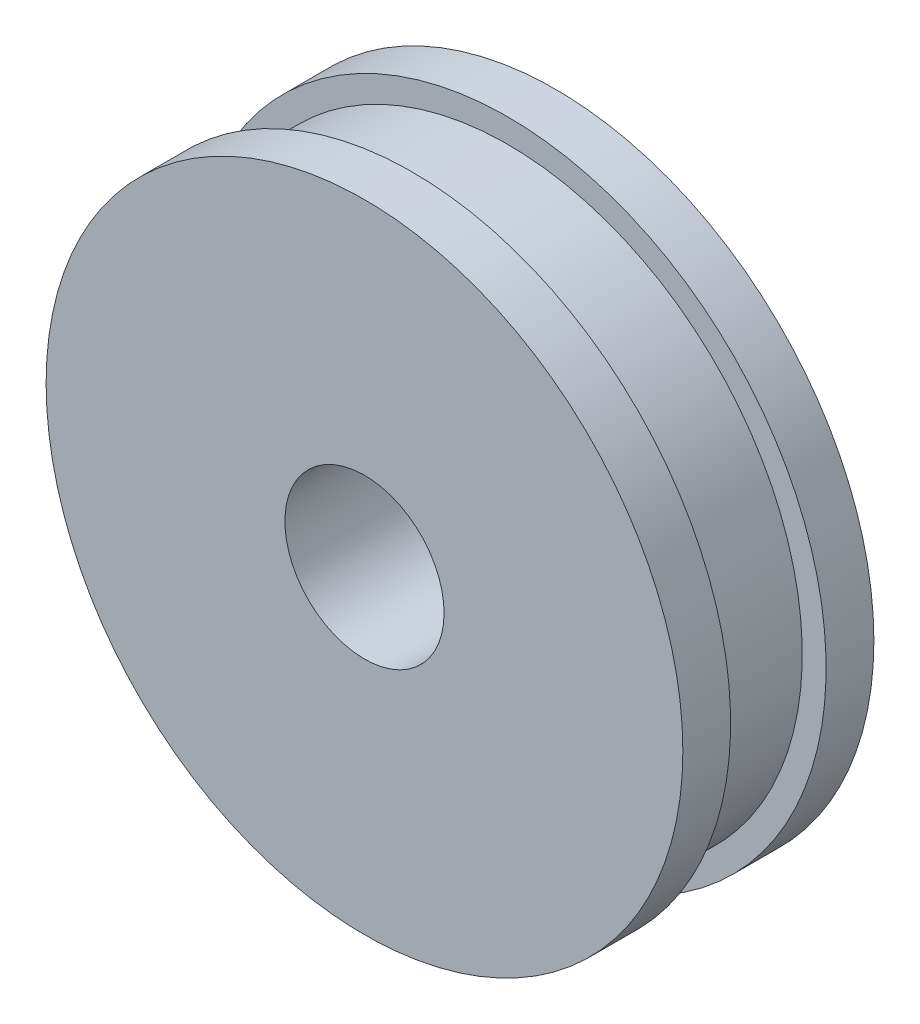
SolidWorks part; units mm, degrees
material "Alumina"
ref_plane "Front Plane" through (0, 0, 0) normal (0, 0, 1) x (1, 0, 0)
ref_plane "Top Plane" through (0, 0, 0) normal (0, 1, 0) x (1, 0, 0)
ref_plane "Right Plane" through (0, 0, 0) normal (1, 0, 0) x (0, 0, -1)
sketch "Sketch1" plane through (0, 0, 0) normal (0, 0, 1) x (1, 0, 0)
  circle A0 centre (0, 0) radius 5
  circle A1 centre (0, 0) radius 20
  dimension "D1" = 10
  dimension "D2" = 40
extrude "Boss-Extrude1" add sketch "Sketch1" along normal blind 12
sketch "Sketch2" plane through (0, 0, 0) normal (0, 1, 0) x (1, 0, 0)
  line L0 (0, 8.6021) -> (0, -18.5227) construction
  line L1 (-20, 0) -> (-20, -12) construction
  line L2 (-20, -3) -> (-18.5, -3)
  line L3 (-20, -3) -> (-20, -9)
  line L4 (-20, -9) -> (-18.5, -9)
  line L5 (-18.5, -3) -> (-18.5, -9)
  line L6 (20, 0) -> (-20, 0) construction
  line L7 (-20, -12) -> (20, -12) construction
  dimension "D1" = 3
  dimension "D2" = 3
  dimension "D3" = 18.5
revolve "Cut-Revolve1" cut sketch "Sketch2" angle 360 about L0
sketch "Sketch3" plane through (0, 0, 0) normal (0, 0, -1) x (-1, 0, 0)
  arc A0 (-2.1788, 4.4892) -> (2.1788, -4.4892) centre (0, 0) ccw
